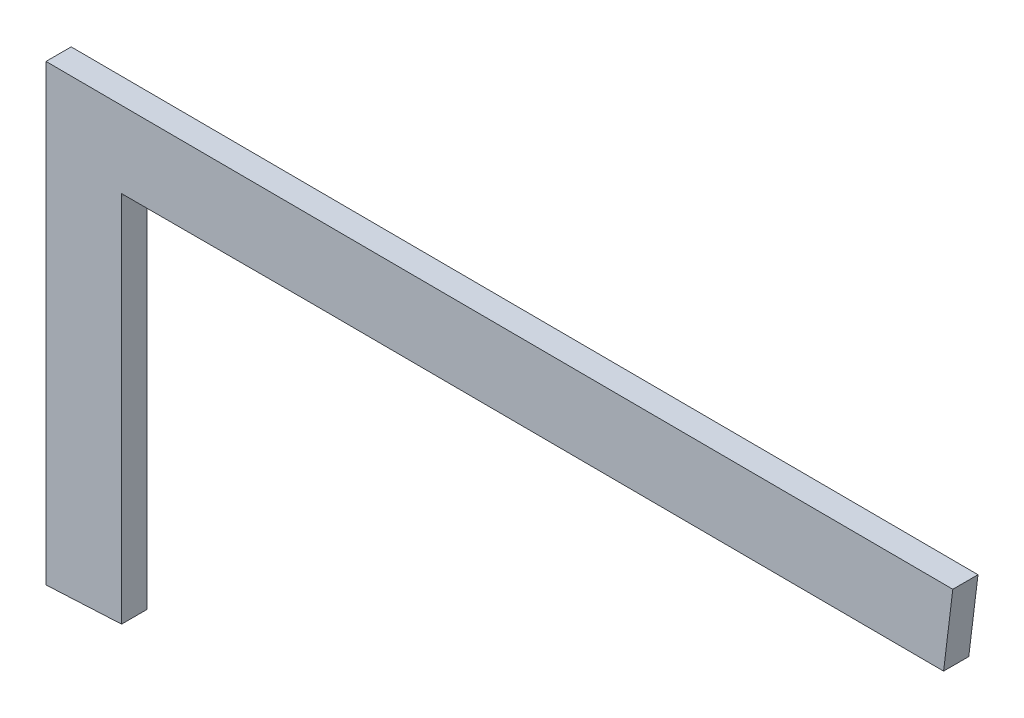
SolidWorks part; units mm, degrees
ref_plane "Plan de face" through (0, 0, 0) normal (0, 0, 1) x (1, 0, 0)
ref_plane "Plan de dessus" through (0, 0, 0) normal (0, 1, 0) x (1, 0, 0)
ref_plane "Plan de droite" through (0, 0, 0) normal (1, 0, 0) x (0, 0, -1)
sketch "Esquisse1" plane through (0, 0, 0) normal (0, 0, 1) x (1, 0, 0)
  line L0 (89.0603, 0.8913) -> (-90.9397, 1.6318)
  line L1 (-90.9397, 1.6318) -> (-90.9397, -88.3682)
  line L3 (87.2305, -14.1013) -> (-37.5613, -13.5879)
  line L4 (-90.9397, -88.3682) -> (-75.9397, -87.6106)
  line L5 (-75.9397, -87.6106) -> (-75.9397, -14.1013)
  line L6 (-37.5613, -13.5879) -> (-75.9438, -13.5879)
  line L7 (-75.9438, -13.5879) -> (-75.9397, -14.1013)
  line L13 (87.2305, -14.1013) -> (89.0603, 0.8913)
  point P2 (-75.9397, -87.6106)
  point P8 (87.2305, -13.5879)
  dimension "D1" = 180
  dimension "D2" = 90
  dimension "D3" = 15
  dimension "D4" = 15
extrude "Boss.-Extru.1" add sketch "Esquisse1" along normal blind 5
